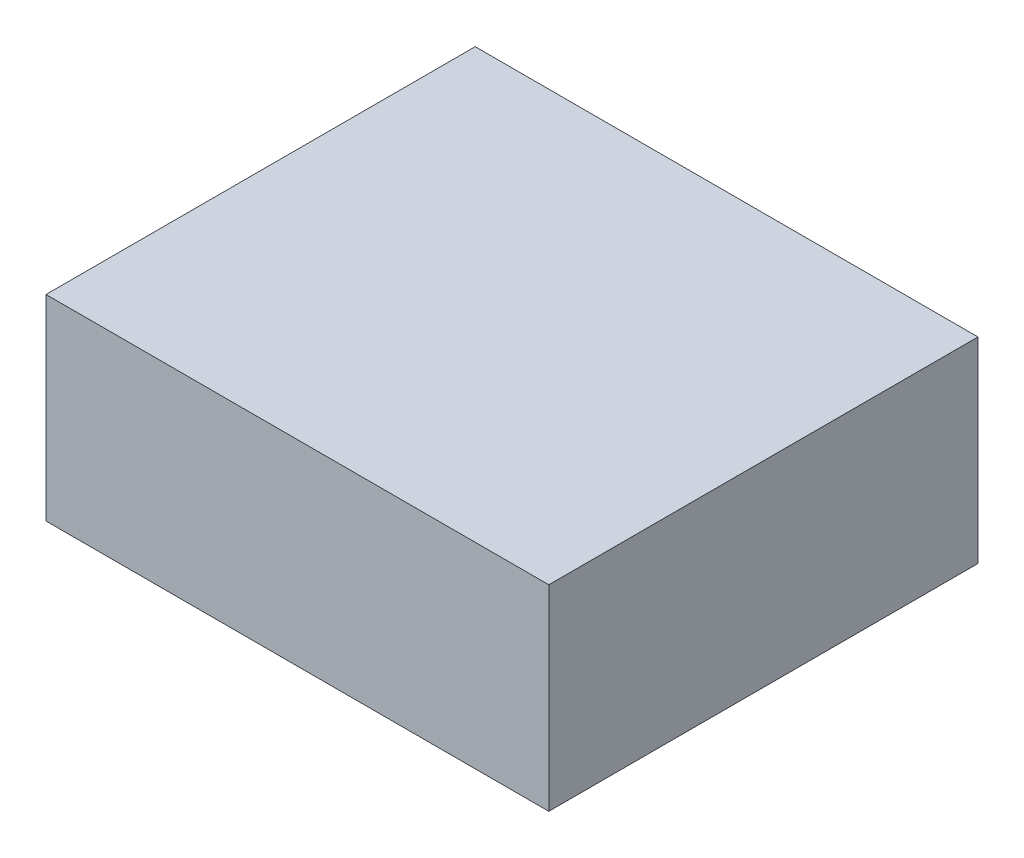
SolidWorks part; units mm, degrees
ref_plane "Front Plane" through (0, 0, 0) normal (0, 0, 1) x (1, 0, 0)
ref_plane "Top Plane" through (0, 0, 0) normal (0, 1, 0) x (1, 0, 0)
ref_plane "Right Plane" through (0, 0, 0) normal (1, 0, 0) x (0, 0, -1)
sketch "Sketch1" plane through (0, 0, 0) normal (0, 1, 0) x (1, 0, 0)
  line L1 (0, 0) -> (41, 0)
  line L2 (0, 0) -> (0, 35)
  line L3 (0, 35) -> (41, 35)
  line L4 (41, 0) -> (41, 35)
  dimension "D1" = 41
  dimension "D2" = 35
extrude "Boss-Extrude1" add sketch "Sketch1" along normal blind 16
